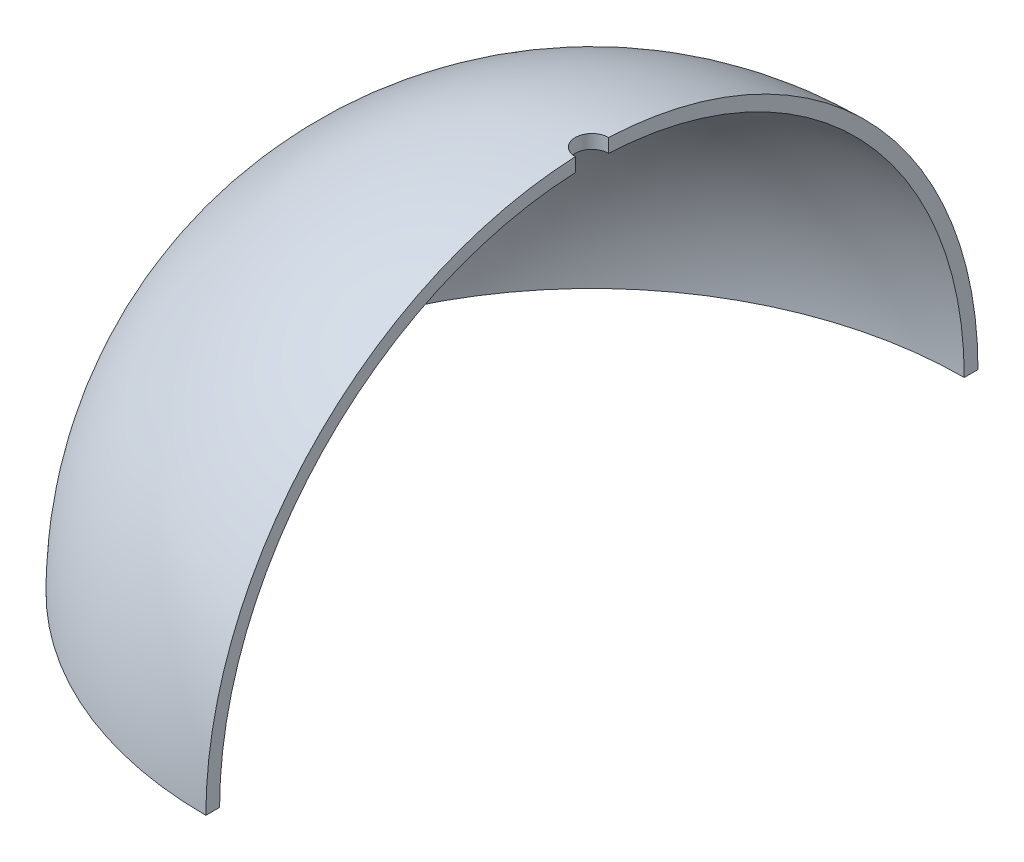
SolidWorks part; units mm, degrees
ref_plane "Front" through (0, 0, 0) normal (0, 0, 1) x (1, 0, 0)
ref_plane "Top" through (0, 0, 0) normal (0, 1, 0) x (1, 0, 0)
ref_plane "Right" through (0, 0, 0) normal (1, 0, 0) x (0, 0, -1)
sketch "Sketch1" plane through (0, 0, 0) normal (0, 1, 0) x (1, 0, 0)
  line L0 (0, 9275) -> (0, 8945)
  line L1 (0, -8945) -> (0, -9275)
  line L3 (0, -41.7154) -> (0, 43.2806) construction
  arc A0 (0, 8945) -> (0, -8945) centre (0, 0) ccw
  arc A1 (0, 9275) -> (0, -9275) centre (0, 0) ccw
  dimension "D1" = 8945
  dimension "D2" = 9275
revolve "Revolve1" add sketch "Sketch1" angle 90 about L3
sketch "Sketch2" plane through (0, 0, 0) normal (0, 1, 0) x (1, 0, 0)
  circle A0 centre (0, 0) radius 400
extrude "Cut-Extrude1" cut sketch "Sketch2" along normal up to surface (9266.3706 mm away)
